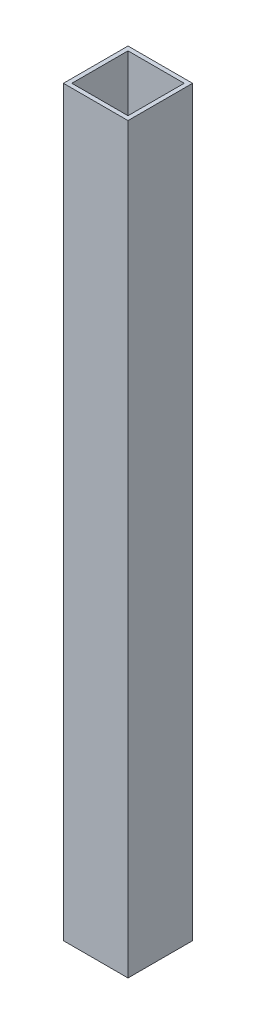
SolidWorks part; units mm, degrees
material "6061 Alloy"
ref_plane "Front Plane" through (0, 0, 0) normal (0, 0, 1) x (1, 0, 0)
ref_plane "Top Plane" through (0, 0, 0) normal (0, 1, 0) x (1, 0, 0)
ref_plane "Right Plane" through (0, 0, 0) normal (1, 0, 0) x (0, 0, -1)
sketch "Sketch1" plane through (0, 0, 0) normal (0, 1, 0) x (1, 0, 0)
  line L1 (-12.7, -12.7) -> (12.7, -12.7)
  line L2 (-12.7, -12.7) -> (-12.7, 12.7)
  line L3 (-12.7, 12.7) -> (12.7, 12.7)
  line L4 (12.7, -12.7) -> (12.7, 12.7)
  line L5 (-12.7, -12.7) -> (12.7, 12.7) construction
  line L6 (-12.7, 12.7) -> (12.7, -12.7) construction
  point P0 (0, 0)
  dimension "D1" = 25.4
  dimension "D2" = 25.4
extrude "Boss-Extrude1" add sketch "Sketch1" along normal mid plane 292.1 contours L2 L1 L4 L3
sketch "Sketch2" plane through (0, 146.05, 0) normal (0, 1, 0) x (1, 0, 0)
  line L0 (-12.7, -12.7) -> (-12.7, 12.7) construction
  line L1 (-11.049, -11.049) -> (11.049, -11.049)
  line L2 (-11.049, -11.049) -> (-11.049, 11.049)
  line L3 (-11.049, 11.049) -> (11.049, 11.049)
  line L4 (11.049, -11.049) -> (11.049, 11.049)
  line L5 (-11.049, -11.049) -> (11.049, 11.049) construction
  line L6 (-11.049, 11.049) -> (11.049, -11.049) construction
  line L7 (-12.7, 12.7) -> (12.7, 12.7) construction
  point P0 (0, 0)
  dimension "D1" = 1.651
  dimension "D2" = 1.651
extrude "Cut-Extrude1" cut sketch "Sketch2" against normal through all contours L2 L1 L4 L3
